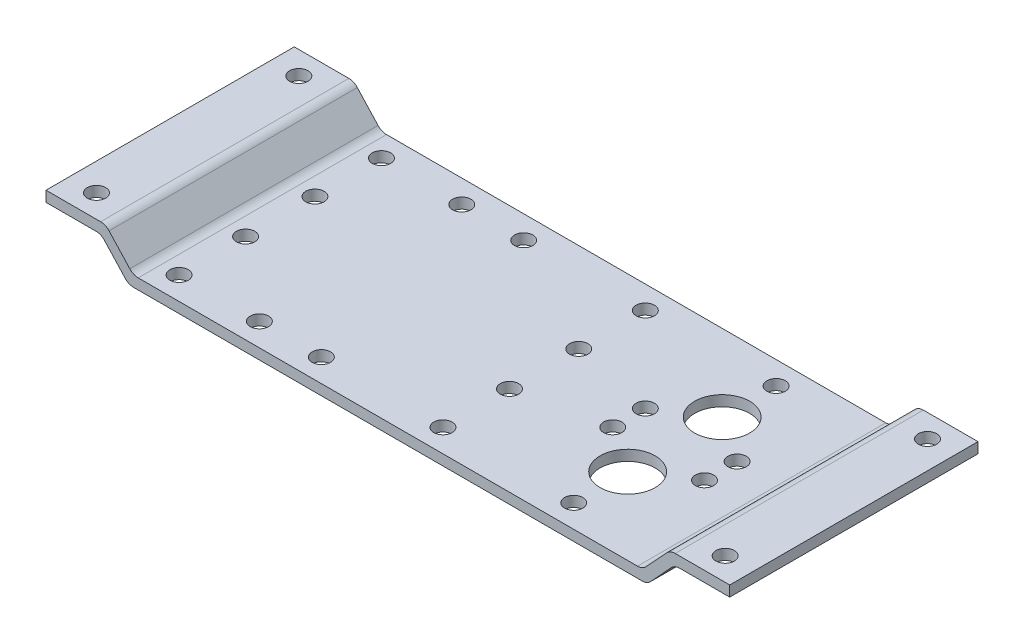
SolidWorks part; units mm, degrees
material "AISI 1020"
ref_plane "Plan de face" through (0, 0, 0) normal (0, 0, 1) x (1, 0, 0)
ref_plane "Plan de dessus" through (0, 0, 0) normal (0, 1, 0) x (1, 0, 0)
ref_plane "Plan de droite" through (0, 0, 0) normal (1, 0, 0) x (0, 0, -1)
sketch "Esquisse1" plane through (0, 0, 0) normal (0, 0, 1) x (1, 0, 0)
  line L0 (0, 0) -> (11.9054, 0)
  line L1 (13.7424, -0.8043) -> (18.2576, -5.6957)
  line L2 (20.0946, -6.5) -> (128.9054, -6.5)
  line L3 (0, -2.3) -> (10.8984, -2.3)
  line L4 (12.7354, -3.1043) -> (17.2506, -7.9957)
  line L5 (19.0876, -8.8) -> (129.9124, -8.8)
  line L6 (0, -2.3) -> (0, 0)
  line L7 (74.5, -8.8) -> (74.5, -6.5) construction
  line L8 (11.993, -2.3) -> (17.993, -8.8) construction
  line L9 (17.993, -8.8) -> (74.5, -8.8) construction
  line L10 (13, 0) -> (19, -6.5) construction
  line L11 (19, -6.5) -> (74.5, -6.5) construction
  line L12 (0, -2.3) -> (11.993, -2.3) construction
  line L13 (0, 0) -> (13, 0) construction
  line L14 (149, -2.3) -> (149, 0)
  line L15 (136.2646, -3.1043) -> (131.7494, -7.9957)
  line L16 (149, -2.3) -> (138.1016, -2.3)
  line L17 (135.2576, -0.8043) -> (130.7424, -5.6957)
  line L18 (149, 0) -> (137.0946, 0)
  arc A0 (17.2506, -7.9957) -> (19.0876, -8.8) centre (19.0876, -6.3) ccw
  arc A1 (18.2576, -5.6957) -> (20.0946, -6.5) centre (20.0946, -4) ccw
  arc A2 (10.8984, -2.3) -> (12.7354, -3.1043) centre (10.8984, -4.8) cw
  arc A3 (11.9054, 0) -> (13.7424, -0.8043) centre (11.9054, -2.5) cw
  arc A4 (137.0946, 0) -> (135.2576, -0.8043) centre (137.0946, -2.5) ccw
  arc A5 (138.1016, -2.3) -> (136.2646, -3.1043) centre (138.1016, -4.8) ccw
  arc A6 (130.7424, -5.6957) -> (128.9054, -6.5) centre (128.9054, -4) cw
  arc A7 (131.7494, -7.9957) -> (129.9124, -8.8) centre (129.9124, -6.3) cw
  point P15 (19, -6.5)
  point P37 (130, -6.5)
  dimension "D6" = 2.5
  dimension "D1" = 74.5
  dimension "D2" = 9.1962
  dimension "D3" = 4
  dimension "D4" = 19
  dimension "D5" = 2.3
extrude "Boss.-Extru.1" add sketch "Esquisse1" along normal blind 54.1
sketch "Esquisse2" plane through (0, 0, 0) normal (0, 1, 0) x (1, 0, 0)
  line L0 (149, -54.1) -> (149, 0) construction
  line L1 (0, -54.1) -> (0, 0) construction
  line L2 (11.9054, 0) -> (0, 0) construction
  line L3 (0, -27.05) -> (149, -27.05) construction
  line L4 (128.9054, 0) -> (20.0946, 0) construction
  circle A0 centre (6, -5) radius 2
  circle A1 centre (24, -5) radius 2
  circle A2 centre (41.5, -5) radius 2
  circle A3 centre (55, -5) radius 2
  circle A4 centre (81.5, -5) radius 2
  circle A5 centre (110, -5) radius 2
  circle A6 centre (143, -5) radius 2
  circle A7 centre (120, -30.6) radius 2
  circle A8 centre (100, -30.6) radius 2
  circle A9 centre (110, -37.35) radius 6
  circle A10 centre (81.5, -34.6) radius 2
  circle A11 centre (24, -34.6) radius 2
  circle A12 centre (143, -49.1) radius 2
  circle A13 centre (110, -49.1) radius 2
  circle A14 centre (24, -19.5) radius 2
  circle A15 centre (81.5, -19.5) radius 2
  circle A16 centre (110, -16.75) radius 6
  circle A17 centre (120, -23.5) radius 2
  circle A18 centre (100, -23.5) radius 2
  circle A19 centre (81.5, -49.1) radius 2
  circle A20 centre (55, -49.1) radius 2
  circle A21 centre (41.5, -49.1) radius 2
  circle A22 centre (24, -49.1) radius 2
  circle A23 centre (6, -49.1) radius 2
  dimension "D1" = 4
  dimension "D12" = 12
  dimension "D2" = 18
  dimension "D3" = 17.5
  dimension "D4" = 13.5
  dimension "D5" = 26.5
  dimension "D6" = 28.5
  dimension "D7" = 6
  dimension "D8" = 6
  dimension "D9" = 5
  dimension "D10" = 14.5
  dimension "D11" = 16.75
  dimension "D13" = 23.5
  dimension "D14" = 29
  dimension "D15" = 10
extrude "Enlèv. mat.-Extru.1" cut sketch "Esquisse2" against normal through all
